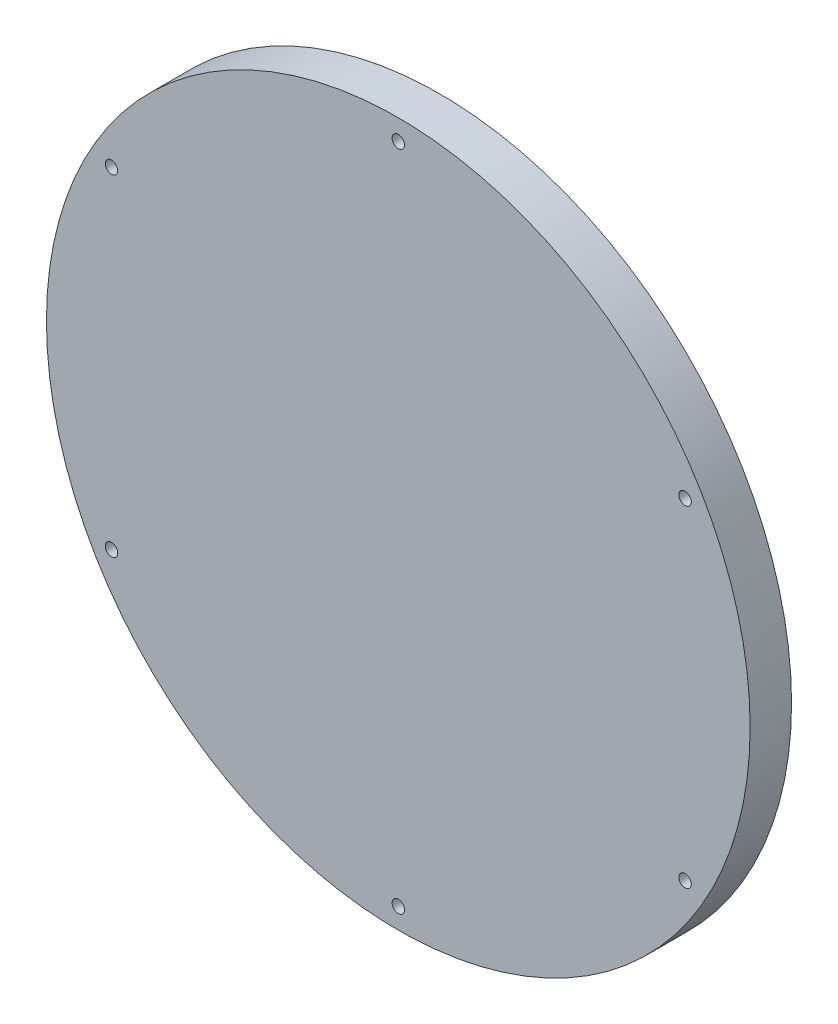
SolidWorks part; units mm, degrees
ref_plane "Ön Düzlem" through (0, 0, 0) normal (0, 0, 1) x (1, 0, 0)
ref_plane "Üst Düzlem" through (0, 0, 0) normal (0, 1, 0) x (1, 0, 0)
ref_plane "Sağ Düzlem" through (0, 0, 0) normal (1, 0, 0) x (0, 0, -1)
sketch "Sketch1" plane through (0, 0, 0) normal (0, 0, 1) x (1, 0, 0)
  circle A0 centre (0, 0) radius 85
  circle A1 centre (0, 0) radius 80 construction
  circle A2 centre (0, 80) radius 1.5
  circle A3 centre (69.282, 40) radius 1.5
  circle A4 centre (69.282, -40) radius 1.5
  circle A5 centre (0, -80) radius 1.5
  circle A6 centre (-69.282, -40) radius 1.5
  circle A7 centre (-69.282, 40) radius 1.5
  dimension "D1" = 170
  dimension "D2" = 160
  dimension "D3" = 3
  dimension "D4" = 6
extrude "Boss-Extrude1" add sketch "Sketch1" along normal blind 10
sketch "Sketch2" plane through (0, 0, 0) normal (0, 1, 0) x (1, 0, 0)
  line L0 (-50, 0) -> (-45, 0)
  line L2 (-50, 0) -> (-50, 4)
  line L3 (-50, 4) -> (50, 4)
  line L4 (50, 0) -> (50, 4)
  line L5 (-45, 2) -> (45, 2)
  line L6 (-45, 2) -> (-45, 0)
  line L7 (45, 2) -> (45, 0)
  line L8 (45, 0) -> (50, 0)
  point P0 (0, 0)
  point P2 (0, 4)
  dimension "D1" = 100
  dimension "D2" = 5
  dimension "D3" = 5
extrude "Boss-Extrude2" add sketch "Sketch2" along normal mid plane 10
